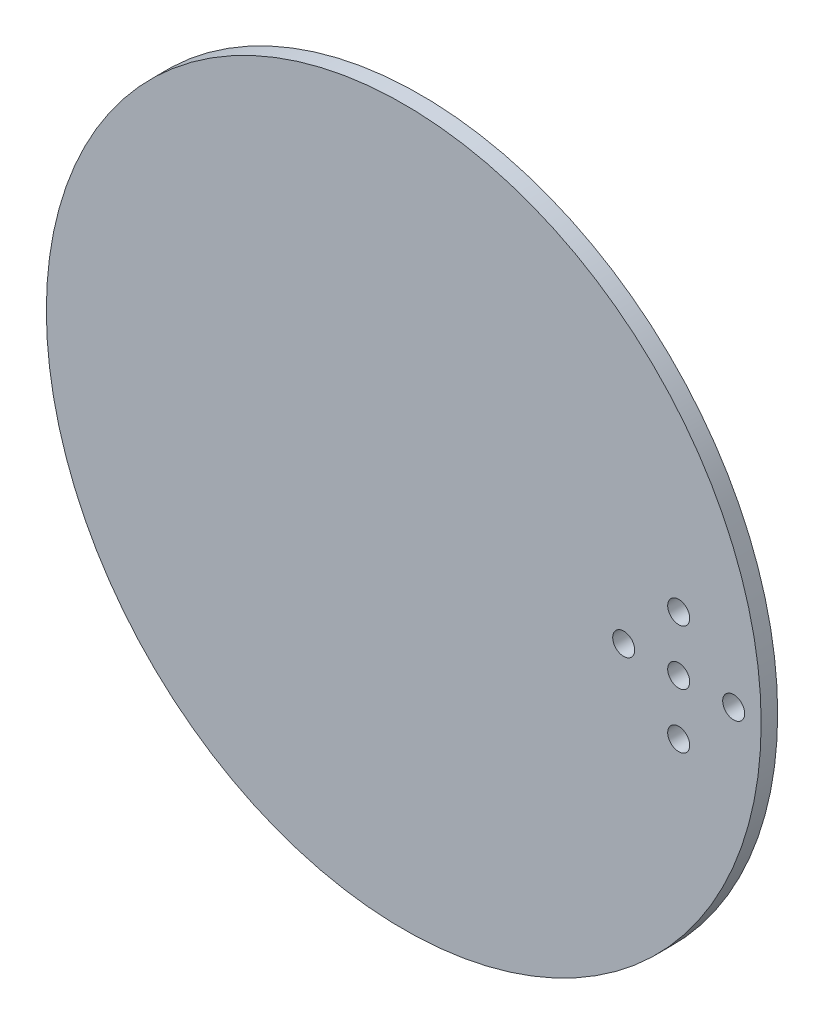
SolidWorks part; units mm, degrees
ref_plane "前视基准面" through (0, 0, 0) normal (0, 0, 1) x (1, 0, 0)
ref_plane "上视基准面" through (0, 0, 0) normal (0, 1, 0) x (1, 0, 0)
ref_plane "右视基准面" through (0, 0, 0) normal (1, 0, 0) x (0, 0, -1)
sketch "草图1" plane through (0, 0, 0) normal (0, 0, 1) x (1, 0, 0)
  circle A0 centre (0, 0) radius 65
  circle A1 centre (0, 0) radius 60 construction
extrude "凸台-拉伸1" add sketch "草图1" along normal blind 3
sketch "草图2" plane through (0, 0, 3) normal (0, 0, 1) x (1, 0, 0)
  line L0 (50, 0) -> (0, 0) construction
  circle A1 centre (50, 0) radius 15
  circle A2 centre (50, 0) radius 1.5
  circle A5 centre (50, 10) radius 2
  circle A6 centre (50, 0) radius 2
  circle A7 centre (50, -10) radius 2
  circle A8 centre (50, 0) radius 10 construction
  circle A9 centre (60, 0) radius 2
  circle A10 centre (40, 0) radius 2
extrude "切除-拉伸4" cut sketch "草图2" against normal blind 3 contours A10 | A7 | A2 | A6 | A5 | A9
